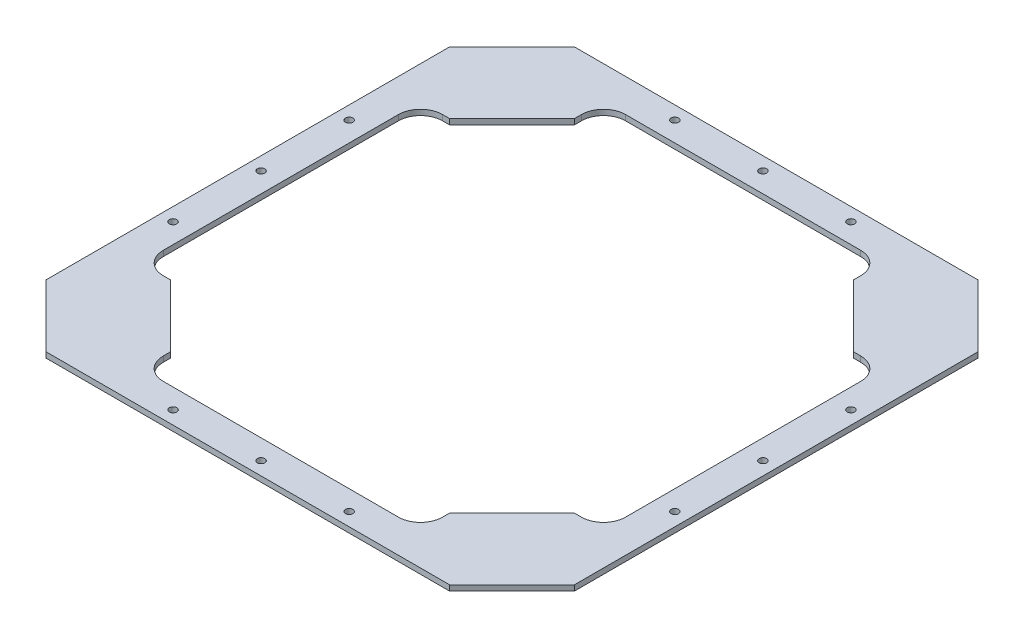
SolidWorks part; units mm, degrees
ref_plane "Front Plane" through (0, 0, 0) normal (0, 0, 1) x (1, 0, 0)
ref_plane "Top Plane" through (0, 0, 0) normal (0, 1, 0) x (1, 0, 0)
ref_plane "Right Plane" through (0, 0, 0) normal (1, 0, 0) x (0, 0, -1)
sketch "Sketch2" plane through (0, 0, 0) normal (0, 1, 0) x (1, 0, 0)
  line L0 (-152.4, 116.479) -> (-116.479, 152.4)
  line L1 (-116.479, 152.4) -> (116.479, 152.4)
  line L2 (-152.4, 116.479) -> (-152.4, -116.479)
  line L3 (-116.479, 80.558) -> (-80.558, 116.479)
  line L4 (-134.4395, 134.4395) -> (-98.5185, 98.5185) construction
  line L5 (-67.858, 133.35) -> (67.858, 133.35)
  line L6 (-133.35, 67.858) -> (-133.35, -67.858)
  line L7 (-116.479, 80.558) -> (-120.65, 80.558)
  line L8 (-80.558, 116.479) -> (-80.558, 120.65)
  line L9 (0, 0) -> (0, 208.1331) construction
  line L10 (0, 0) -> (-190.1851, 0) construction
  line L11 (133.35, 67.858) -> (133.35, -67.858)
  line L12 (152.4, 116.479) -> (152.4, -116.479)
  line L13 (134.4395, 134.4395) -> (98.5185, 98.5185) construction
  line L14 (80.558, 116.479) -> (80.558, 120.65)
  line L15 (116.479, 80.558) -> (120.65, 80.558)
  line L16 (116.479, 80.558) -> (80.558, 116.479)
  line L17 (152.4, 116.479) -> (116.479, 152.4)
  line L18 (134.4395, -134.4395) -> (98.5185, -98.5185) construction
  line L19 (-134.4395, -134.4395) -> (-98.5185, -98.5185) construction
  line L20 (152.4, -116.479) -> (116.479, -152.4)
  line L21 (116.479, -80.558) -> (80.558, -116.479)
  line L22 (116.479, -80.558) -> (120.65, -80.558)
  line L23 (80.558, -116.479) -> (80.558, -120.65)
  line L24 (-80.558, -116.479) -> (-80.558, -120.65)
  line L25 (-116.479, -80.558) -> (-120.65, -80.558)
  line L26 (-67.858, -133.35) -> (67.858, -133.35)
  line L27 (-116.479, -80.558) -> (-80.558, -116.479)
  line L28 (-116.479, -152.4) -> (116.479, -152.4)
  line L29 (-152.4, -116.479) -> (-116.479, -152.4)
  arc A0 (-80.558, 120.65) -> (-67.858, 133.35) centre (-67.858, 120.65) cw
  arc A1 (-120.65, 80.558) -> (-133.35, 67.858) centre (-120.65, 67.858) ccw
  arc A2 (120.65, 80.558) -> (133.35, 67.858) centre (120.65, 67.858) cw
  arc A3 (80.558, 120.65) -> (67.858, 133.35) centre (67.858, 120.65) ccw
  arc A4 (80.558, -120.65) -> (67.858, -133.35) centre (67.858, -120.65) cw
  arc A5 (120.65, -80.558) -> (133.35, -67.858) centre (120.65, -67.858) ccw
  arc A6 (-120.65, -80.558) -> (-133.35, -67.858) centre (-120.65, -67.858) cw
  arc A7 (-80.558, -120.65) -> (-67.858, -133.35) centre (-67.858, -120.65) ccw
  point P23 (133.35, 0)
  point P25 (0, 133.35)
  point P26 (0, 152.4)
  point P54 (152.4, 0)
  point P56 (-133.35, 0)
  point P57 (-152.4, 0)
  point P58 (0, -152.4)
  point P59 (0, -133.35)
  dimension "D10" = 12.7
  dimension "D1" = 50.8
  dimension "D2" = 152.4
  dimension "D3" = 152.4
  dimension "D4" = 50.8
  dimension "D5" = 19.05
  dimension "D6" = 19.05
  dimension "D7" = 45
  dimension "D8" = 45
  dimension "D9" = 50.8
extrude "Boss-Extrude1" add sketch "Sketch2" along normal blind 3.175
sketch "Sketch4" plane through (0, 3.175, 0) normal (0, 1, 0) x (1, 0, 0)
  line L0 (0, 201.0925) -> (0, -226.4518) construction
  line L1 (-181.7718, 0) -> (192.408, 0) construction
  line L2 (116.479, 152.4) -> (-116.479, 152.4) construction
  line L3 (-152.4, 116.479) -> (-152.4, -116.479) construction
  circle A0 centre (0, 144.78) radius 2.159
  circle A1 centre (-50.8, 144.78) radius 2.159
  circle A2 centre (-144.78, 50.8) radius 2.159
  circle A3 centre (-144.78, 0) radius 2.159
  circle A4 centre (144.78, 0) radius 2.159
  circle A5 centre (144.78, 50.8) radius 2.159
  circle A6 centre (50.8, 144.78) radius 2.159
  circle A7 centre (50.8, -144.78) radius 2.159
  circle A8 centre (144.78, -50.8) radius 2.159
  circle A9 centre (-50.8, -144.78) radius 2.159
  circle A10 centre (0, -144.78) radius 2.159
  circle A11 centre (-144.78, -50.8) radius 2.159
  dimension "D1" = 4.318
  dimension "D2" = 4.318
  dimension "D3" = 4.318
  dimension "D4" = 4.318
  dimension "D5" = 7.62
  dimension "D6" = 7.62
  dimension "D7" = 50.8
  dimension "D8" = 7.62
  dimension "D9" = 7.62
  dimension "D10" = 50.8
extrude "Cut-Extrude2" cut sketch "Sketch4" against normal through all
